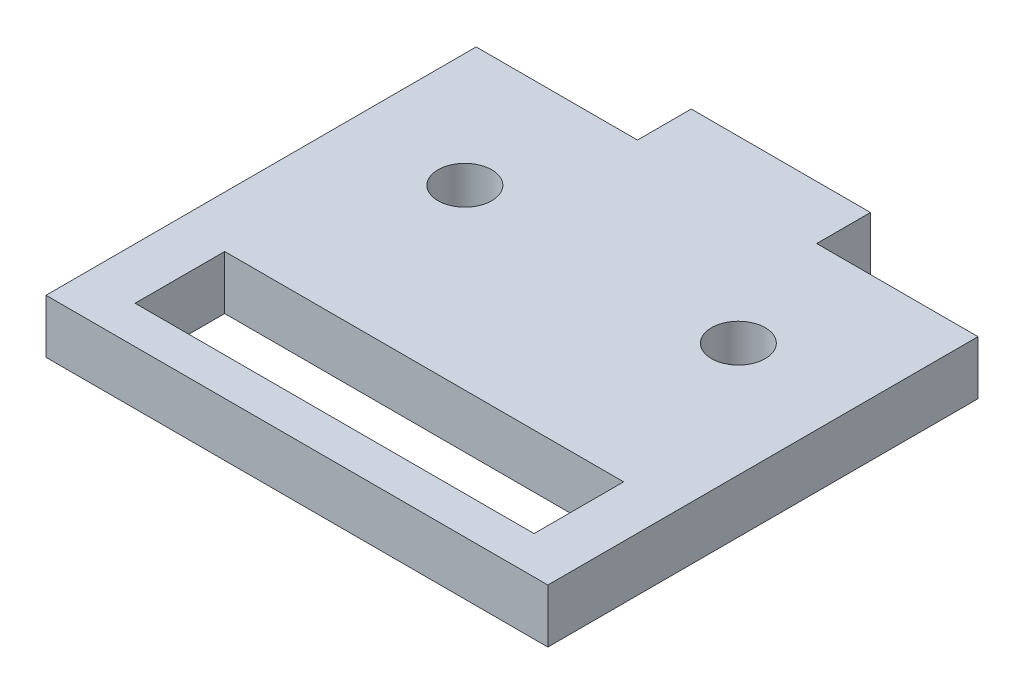
SolidWorks part; units mm, degrees
ref_plane "Front Plane" through (0, 0, 0) normal (0, 0, 1) x (1, 0, 0)
ref_plane "Top Plane" through (0, 0, 0) normal (0, 1, 0) x (1, 0, 0)
ref_plane "Right Plane" through (0, 0, 0) normal (1, 0, 0) x (0, 0, -1)
sketch "Sketch1" plane through (0, 0, 0) normal (0, 1, 0) x (1, 0, 0)
  line L0 (-5, 3) -> (5, 3)
  line L2 (5, 3) -> (14, 3)
  line L3 (14, 3) -> (14, 27)
  line L4 (14, 27) -> (5, 27)
  line L5 (11.13, 5.1) -> (11.13, 10.1)
  line L6 (11.13, 10.1) -> (-11.13, 10.1)
  line L7 (5, 27) -> (5, 30)
  line L8 (-11.13, 5.1) -> (11.13, 5.1)
  line L9 (0, 25) -> (0, 10.1) construction
  line L10 (-11.13, 5.1) -> (-11.13, 10.1)
  line L11 (-14, 3) -> (-14, 27)
  line L12 (-5, 3) -> (-14, 3)
  line L15 (5, 30) -> (-5, 30)
  line L16 (-5, 30) -> (-5, 27)
  line L17 (-5, 27) -> (-14, 27)
  circle A0 centre (7.63, 20) radius 1.5
  circle A1 centre (-7.63, 20) radius 1.5
  point P2 (-5.1163, -0.6118)
  point P12 (-0.5244, -1.2838)
  dimension "D9" = 3
  dimension "D2" = 10
  dimension "D3" = 9
  dimension "D4" = 6.37
  dimension "D5" = 7
  dimension "D6" = 24
  dimension "D7" = 2.1
  dimension "D8" = 5
  dimension "D10" = 22.26
  dimension "D11" = 3
  dimension "D12" = 10
  dimension "D13" = 3
  dimension "D14" = 14
extrude "Boss-Extrude1" add sketch "Sketch1" along normal blind 3
